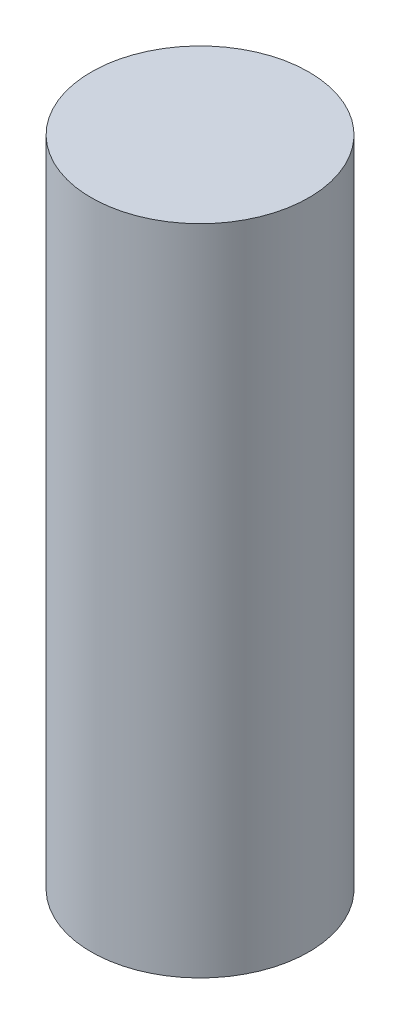
SolidWorks part; units mm, degrees
ref_plane "Front Plane" through (0, 0, 0) normal (0, 0, 1) x (1, 0, 0)
ref_plane "Top Plane" through (0, 0, 0) normal (0, 1, 0) x (1, 0, 0)
ref_plane "Right Plane" through (0, 0, 0) normal (1, 0, 0) x (0, 0, -1)
sketch "Sketch1" plane through (0, 0, 0) normal (0, 1, 0) x (1, 0, 0)
  circle A0 centre (0, 0) radius 6.35
extrude "Boss-Extrude1" add sketch "Sketch1" along normal blind 38.1
